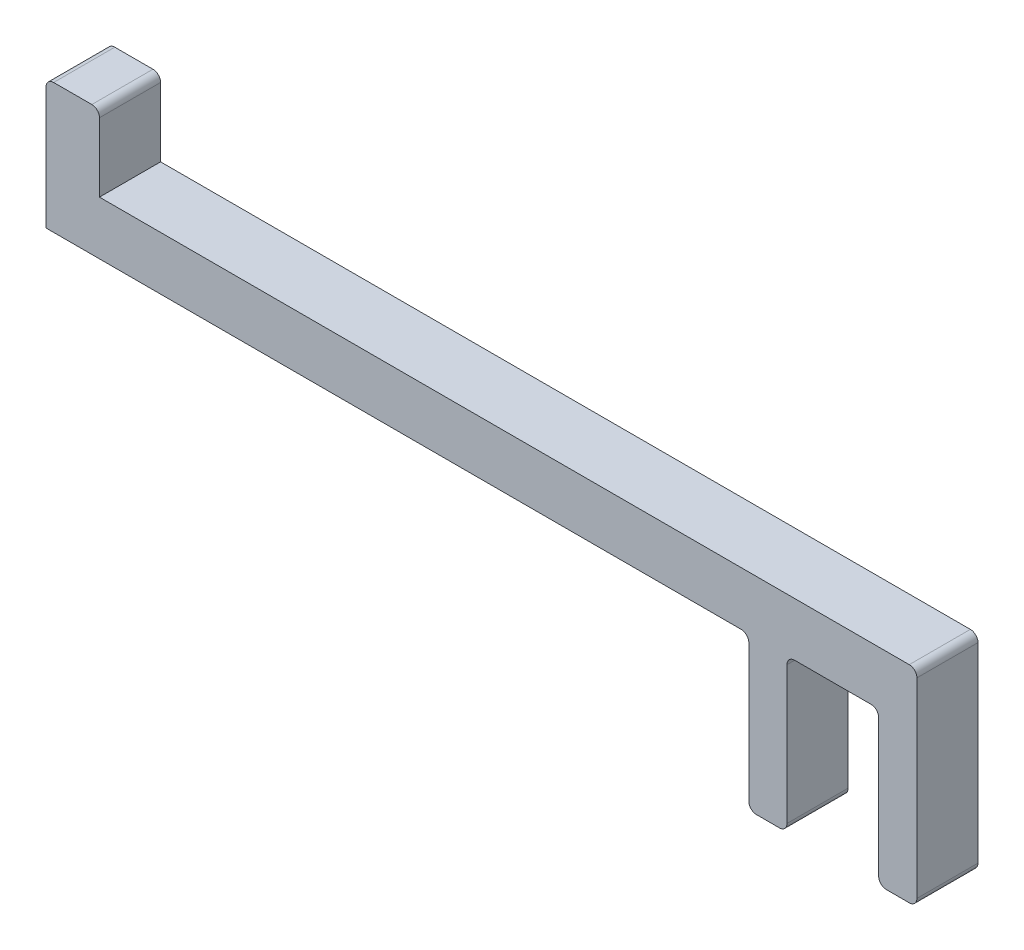
SolidWorks part; units mm, degrees
ref_plane "Спереди" through (0, 0, 0) normal (0, 0, 1) x (1, 0, 0)
ref_plane "Сверху" through (0, 0, 0) normal (0, 1, 0) x (1, 0, 0)
ref_plane "Справа" through (0, 0, 0) normal (1, 0, 0) x (0, 0, -1)
sketch "Эскиз1" plane through (0, 0, 0) normal (0, 0, 1) x (1, 0, 0)
  line L1 (-47.7343, 17) -> (-42.7343, 17)
  line L2 (-41.7343, 16) -> (-41.7343, 7)
  line L3 (-41.7343, 7) -> (25.2299, 7)
  line L5 (43.2657, -1) -> (43.2657, -19)
  line L6 (44.2657, -20) -> (47.2657, -20)
  line L7 (48.2657, -19) -> (48.2657, -1)
  line L8 (49.2657, 0) -> (59.2657, 0)
  line L9 (60.2657, -1) -> (60.2657, -19)
  line L10 (61.2657, -20) -> (64.2657, -20)
  line L11 (65.2657, -19) -> (65.2657, 6)
  line L12 (64.2657, 7) -> (25.2299, 7)
  line L13 (42.2657, 0) -> (-48.7343, 0)
  line L14 (-48.7343, 16) -> (-48.7343, 0)
  arc A0 (59.2657, 0) -> (60.2657, -1) centre (59.2657, -1) cw
  arc A1 (48.2657, -1) -> (49.2657, 0) centre (49.2657, -1) cw
  arc A2 (43.2657, -19) -> (44.2657, -20) centre (44.2657, -19) ccw
  arc A3 (47.2657, -20) -> (48.2657, -19) centre (47.2657, -19) ccw
  arc A4 (60.2657, -19) -> (61.2657, -20) centre (61.2657, -19) ccw
  arc A5 (64.2657, -20) -> (65.2657, -19) centre (64.2657, -19) ccw
  arc A7 (-42.7343, 17) -> (-41.7343, 16) centre (-42.7343, 16) cw
  arc A8 (-48.7343, 16) -> (-47.7343, 17) centre (-47.7343, 16) cw
  arc A9 (65.2657, 6) -> (64.2657, 7) centre (64.2657, 6) ccw
  arc A10 (42.2657, 0) -> (43.2657, -1) centre (42.2657, -1) cw
  point P17 (60.2657, 0)
  point P20 (48.2657, 0)
  point P23 (43.2657, -20)
  point P26 (48.2657, -20)
  point P29 (60.2657, -20)
  point P32 (65.2657, -20)
  point P34 (43.2657, 0)
  point P35 (0, 0)
  point P38 (-41.7343, 17)
  point P41 (-104.9642, 40)
  point P44 (54.2657, 0)
  point P45 (-41.7343, 11.5)
  dimension "D8" = 1
  dimension "D9" = 1
  dimension "D1" = 1
  dimension "D2" = 7
  dimension "D3" = 90
  dimension "D4" = 20
  dimension "D5" = 12
  dimension "D6" = 5
  dimension "D7" = 5
  dimension "D10" = 5
  dimension "D11" = 20
  dimension "D12" = 7
  dimension "D13" = 17
  dimension "18" = 18
extrude "Бобышка-Вытянуть1" add sketch "Эскиз1" along normal blind 12
sketch "Эскиз2" plane through (0, 17, 0) normal (0, 1, 0) x (1, 0, 0)
  line L0 (81.4238, -4) -> (-154.4729, -4)
  line L1 (64.2657, 0) -> (-41.7343, 0) construction
  line L8 (81.4238, -16) -> (-154.4729, -16)
  line L9 (-154.4729, -4) -> (-146.3488, 32.6062)
  line L10 (-146.3488, 32.6062) -> (92.9575, 29.2357)
  line L11 (81.4238, -4) -> (92.9575, 29.2357)
  line L12 (81.4238, -16) -> (103.3098, -54.5455)
  line L13 (103.3098, -54.5455) -> (-172.1121, -50.6664)
  line L14 (-154.4729, -16) -> (-172.1121, -50.6664)
  dimension "D1" = 12
  dimension "D2" = 4
extrude "Вырез-Вытянуть1" cut sketch "Эскиз2" against normal blind 82
